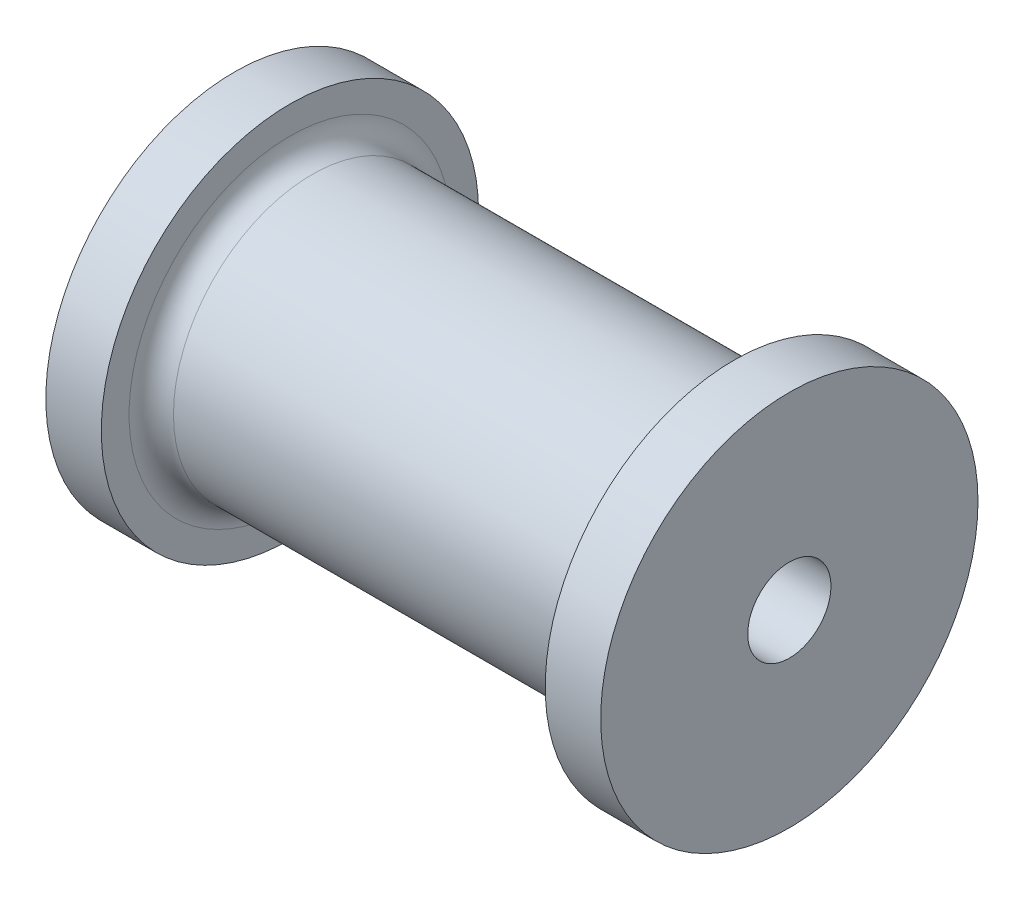
SolidWorks part; units mm, degrees
material "ABS PC"
ref_plane "Front Plane" through (0, 0, 0) normal (0, 0, 1) x (1, 0, 0)
ref_plane "Top Plane" through (0, 0, 0) normal (0, 1, 0) x (1, 0, 0)
ref_plane "Right Plane" through (0, 0, 0) normal (1, 0, 0) x (0, 0, -1)
sketch "Sketch1" plane through (0, 0, 0) normal (1, 0, 0) x (0, 0, -1)
  circle A0 centre (0, 0) radius 21.59
  dimension "D1" = 43.18
extrude "Boss-Extrude1" add sketch "Sketch1" along normal blind 6.35
sketch "Sketch2" plane through (6.35, 0, 0) normal (1, 0, 0) x (0, 0, -1)
  circle A0 centre (0, 0) radius 15.875
  dimension "D1" = 31.75
extrude "Boss-Extrude2" add sketch "Sketch2" along normal blind 50.8
sketch "Sketch3" plane through (57.15, 0, 0) normal (1, 0, 0) x (0, 0, -1)
  circle A1 centre (0, 0) radius 21.59
  dimension "D1" = 43.18
fillet "Fillet1" radius 2.54 1 edges at (6.35, 0, -15.875)
extrude "Boss-Extrude3" add sketch "Sketch3" along normal blind 6.35
fillet "Fillet2" radius 2.54 1 edges at (57.15, 0, -15.875)
sketch "Sketch4" plane through (63.5, 0, 0) normal (1, 0, 0) x (0, 0, -1)
  circle A0 centre (0, 0) radius 4.7625
  dimension "D1" = 9.525
extrude "Cut-Extrude1" cut sketch "Sketch4" against normal through all
equation "\"D1@Sketch3\"=\"D1@Sketch1\""
